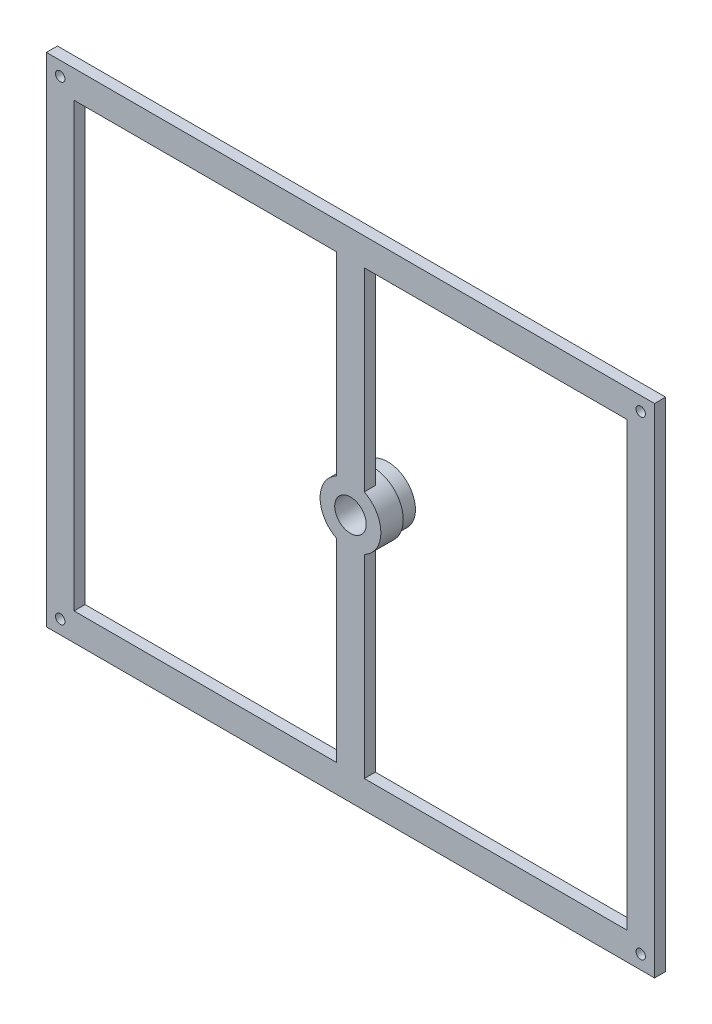
SolidWorks part; units mm, degrees
material "6061-T6 (SS)"
ref_plane "Front Plane" through (0, 0, 0) normal (0, 0, 1) x (1, 0, 0)
ref_plane "Top Plane" through (0, 0, 0) normal (0, 1, 0) x (1, 0, 0)
ref_plane "Right Plane" through (0, 0, 0) normal (1, 0, 0) x (0, 0, -1)
sketch "Sketch1" plane through (0, 0, 0) normal (0, 0, 1) x (1, 0, 0)
  line L1 (-110, -90) -> (110, -90)
  line L2 (-110, -90) -> (-110, 90)
  line L3 (-110, 90) -> (110, 90)
  line L4 (110, -90) -> (110, 90)
  line L6 (-100, -80) -> (100, -80)
  line L7 (-100, -80) -> (-100, 80)
  line L8 (-100, 80) -> (100, 80)
  line L9 (100, -80) -> (100, 80)
extrude "Upper_Perimeter" add sketch "Sketch1" along normal blind 4 from offset 304
sketch "Sketch2" plane through (0, 0, 0) normal (0, 0, 1) x (1, 0, 0)
  line L1 (-5, -85) -> (5, -85)
  line L2 (-5, -85) -> (-5, 85)
  line L3 (-5, 85) -> (5, 85)
  line L4 (5, -85) -> (5, 85)
extrude "Bearing_Spine" add sketch "Sketch2" along normal blind 4 from offset 304
sketch "Sketch3" plane through (0, 0, 0) normal (0, 0, 1) x (1, 0, 0)
  circle A0 centre (0, 0) radius 11
  circle A1 centre (0, 0) radius 5.7
extrude "Upper_Outer_Race_Stop" add sketch "Sketch3" along normal blind 8.1 from offset 299.9
sketch "Sketch4" plane through (0, 0, 0) normal (0, 0, 1) x (1, 0, 0)
  circle A0 centre (0, 0) radius 10
  circle A1 centre (0, 0) radius 6.5
extrude "Floating_Outer_Race_Seat" add sketch "Sketch4" along normal blind 5.41 from offset 294.5
sketch "Sketch5" plane through (0, 0, 308) normal (0, 0, 1) x (1, 0, 0)
  circle A0 centre (0, 0) radius 5.7
extrude "Shaft_Clip_Clearance" cut sketch "Sketch5" against normal blind 8.11
sketch "Sketch6" plane through (0, 0, 308) normal (0, 0, 1) x (1, 0, 0)
  circle A0 centre (-105, -85) radius 1.7
  circle A1 centre (-105, 85) radius 1.7
  circle A2 centre (105, -85) radius 1.7
  circle A3 centre (105, 85) radius 1.7
extrude "Four_Tie_Rod_Clearance" cut sketch "Sketch6" against normal blind 4.01
sketch "Sketch7" plane through (0, 0, 294.5) normal (0, 0, -1) x (-1, 0, 0)
  circle A0 centre (-7.188, 4.15) radius 1
  circle A1 centre (7.188, 4.15) radius 1
  circle A2 centre (0, -8.3) radius 1
extrude "Three_M2_Top_Cap_Thread_Major_Envelopes" cut sketch "Sketch7" against normal blind 4.3
